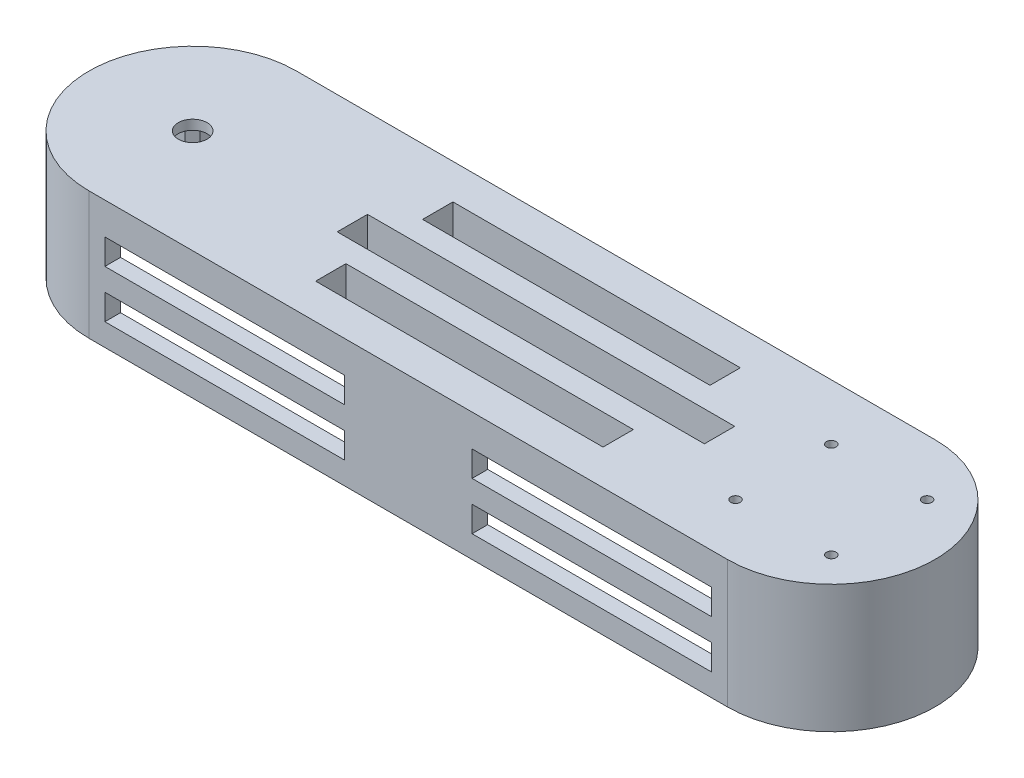
SolidWorks part; units mm, degrees
ref_plane "Front Plane" through (0, 0, 0) normal (0, 0, 1) x (1, 0, 0)
ref_plane "Top Plane" through (0, 0, 0) normal (0, 1, 0) x (1, 0, 0)
ref_plane "Right Plane" through (0, 0, 0) normal (1, 0, 0) x (0, 0, -1)
sketch "Sketch1" plane through (0, 0, 0) normal (0, 1, 0) x (1, 0, 0)
  line L0 (-100, 32.5) -> (100, 32.5)
  line L1 (-100, -32.5) -> (100, -32.5)
  line L6 (0, 21.5) -> (-40, 21.5)
  line L7 (-40, 21.5) -> (-40, 12)
  line L8 (-40, 12) -> (0, 12)
  line L9 (0, 12) -> (50, 12)
  line L10 (50, 12) -> (50, 21.5)
  line L11 (50, 21.5) -> (0, 21.5)
  line L12 (-50, 4.75) -> (0, 4.75)
  line L13 (0, 4.75) -> (65, 4.75)
  line L14 (65, 4.75) -> (65, -4.75)
  line L15 (65, -4.75) -> (0, -4.75)
  line L16 (0, -4.75) -> (-50, -4.75)
  line L17 (-50, -4.75) -> (-50, 4.75)
  line L21 (0, -12) -> (-40, -12)
  line L22 (-40, -12) -> (-40, -21.5)
  line L23 (-40, -21.5) -> (0, -21.5)
  line L24 (0, -21.5) -> (50, -21.5)
  line L25 (50, -21.5) -> (50, -12)
  line L26 (50, -12) -> (0, -12)
  line L27 (100, 13.6373) -> (100, -13.3202) construction
  line L28 (82.1775, 0) -> (117.959, 0) construction
  arc A0 (100, 32.5) -> (100, -32.5) centre (100, 0) cw
  arc A1 (-100, 32.5) -> (-100, -32.5) centre (-100, 0) ccw
  circle A10 centre (85, 15) radius 1.5
  circle A11 centre (115, 15) radius 1.5
  circle A12 centre (85, -15) radius 1.5
  circle A13 centre (115, -15) radius 1.5
  dimension "D5" = 3
  dimension "D6" = 15
  dimension "D7" = 4.75
  dimension "D8" = 15
  dimension "D1" = 32.5
  dimension "D2" = 32.5
  dimension "D3" = 100
  dimension "D4" = 100
  dimension "D25" = 9.5
  dimension "D26" = 9.5
  dimension "D27" = 9.5
  dimension "D28" = 50
  dimension "D29" = 0
  dimension "D30" = 0
  dimension "D31" = 40
  dimension "D32" = 65
  dimension "D33" = 0
  dimension "D34" = 0
  dimension "D35" = 50
  dimension "D36" = 40
  dimension "D37" = 0
  dimension "D38" = 0
  dimension "D39" = 50
  dimension "D40" = 11
  dimension "D41" = 11
extrude "Boss-Extrude1" add sketch "Sketch1" along normal blind 10
sketch "Sketch2" plane through (0, 0, 0) normal (0, 1, 0) x (1, 0, 0)
  line L0 (-100, 32.5) -> (100, 32.5)
  line L1 (100, -32.5) -> (-100, -32.5)
  line L4 (99.6685, 27.511) -> (-100, 27.511)
  line L5 (-100, -27.6007) -> (100.9985, -27.6007)
  arc A0 (100, 32.5) -> (100, -32.5) centre (100, 0) cw
  arc A1 (-100, 32.5) -> (-100, -32.5) centre (-100, 0) ccw
  arc A3 (99.6685, 27.511) -> (100.9985, -27.6007) centre (100.9985, -0.0288) cw
  arc A4 (-100, 27.511) -> (-100, -27.6007) centre (-100, -0.0449) ccw
  dimension "D3" = 5
  dimension "D4" = 5
extrude "Boss-Extrude2" add sketch "Sketch2" against normal blind 30
sketch "Sketch3" plane through (0, 0, 0) normal (0, 0, 1) x (1, 0, 0)
  line L7 (-95, -23) -> (-95, -15)
  line L10 (95, -15) -> (95, -23)
  line L24 (95, 0) -> (95, -8)
  line L27 (-95, -8) -> (-95, 0)
  line L28 (-20, 0) -> (-95, 0)
  line L29 (-95, -8) -> (-20, -8)
  line L30 (-20, -8) -> (-20, 0)
  line L31 (-95, -23) -> (-20, -23)
  line L32 (-20, -23) -> (-20, -15)
  line L33 (-20, -15) -> (-95, -15)
  line L34 (20, 0) -> (20, -8)
  line L35 (20, -8) -> (95, -8)
  line L36 (95, 0) -> (20, 0)
  line L37 (20, -15) -> (20, -23)
  line L38 (20, -23) -> (95, -23)
  line L39 (95, -15) -> (20, -15)
  line L40 (100, 10) -> (100, -30) construction
  line L41 (-100, 10) -> (-100, -30) construction
  line L42 (-100, 10) -> (100, 10) construction
  line L43 (-100, -30) -> (100, -30) construction
  point P16 (-20, -4)
  point P20 (95, -19)
  point P23 (-95, -4)
  dimension "D1" = 8
  dimension "D2" = 8
  dimension "D3" = 20
  dimension "D4" = 20
  dimension "D5" = 0
  dimension "D6" = 5
  dimension "D7" = 0
  dimension "D8" = 5
  dimension "D9" = 0
  dimension "D10" = 10
  dimension "D11" = 7
  dimension "D12" = 7
  dimension "D13" = 8
  dimension "D14" = 8
  dimension "D15" = 10
extrude "Cut-Extrude1" cut sketch "Sketch3" against normal mid plane 90
sketch "Sketch4" plane through (0, 0, 0) normal (0, 1, 0) x (1, 0, 0)
  line L0 (0, 0) -> (-141.2998, 0) construction
  line L1 (-100, 32.5) -> (-100, -32.5) construction
  line L2 (-102, 19) -> (-98, 19)
  line L3 (-98, 19) -> (-95.5, 4.5)
  line L4 (-95.5, 4.5) -> (-81, 2)
  line L5 (-81, 2) -> (-81, -2)
  line L6 (-100, 0) -> (-115.0821, 0) construction
  line L7 (-95.5, -4.5) -> (-81, -2)
  line L8 (-98, -19) -> (-95.5, -4.5)
  line L9 (-102, -19) -> (-98, -19)
  line L10 (-102, 19) -> (-104.5, 4.5)
  line L11 (-104.5, 4.5) -> (-119, 2)
  line L12 (-119, 2) -> (-119, -2)
  line L13 (-104.5, -4.5) -> (-119, -2)
  line L14 (-102, -19) -> (-104.5, -4.5)
  point P15 (-81, 0)
  point P19 (-100, 19)
  point P24 (-100, -19)
  dimension "D1" = 19
  dimension "D2" = 19
  dimension "D3" = 2
  dimension "D4" = 2
  dimension "D5" = 4.5
  dimension "D6" = 4.5
extrude "Cut-Extrude2" cut sketch "Sketch4" along normal blind 7
sketch "Sketch5" plane through (0, 0, 0) normal (0, 1, 0) x (1, 0, 0)
  circle A1 centre (-100, 0) radius 4.5
  dimension "D1" = 9
extrude "Cut-Extrude3" cut sketch "Sketch5" along normal blind 10
sketch "Sketch7" plane through (0, 0, 0) normal (0, -1, 0) x (1, 0, 0)
  line L0 (-106.5, 4.1552) -> (-106.5, -4.1552)
  line L1 (-119, 2) -> (-104.5, 4.5) construction
  line L2 (-106.5, 4.1552) -> (-104.1552, 6.5)
  line L3 (-104.5, 4.5) -> (-102, 19) construction
  line L4 (-104.1552, 6.5) -> (-95.8448, 6.5)
  line L5 (-100, 6.601) -> (-100, -6.364) construction
  line L6 (-106.364, 0) -> (-93.636, 0) construction
  line L7 (-93.5, 4.1552) -> (-95.8448, 6.5)
  line L8 (-93.5, 4.1552) -> (-93.5, -4.1552)
  line L9 (-93.5, -4.1552) -> (-95.8448, -6.5)
  line L10 (-104.1552, -6.5) -> (-95.8448, -6.5)
  line L11 (-106.5, -4.1552) -> (-104.1552, -6.5)
  dimension "D3" = 6.5
extrude "Cut-Extrude4" cut sketch "Sketch7" against normal blind 7
